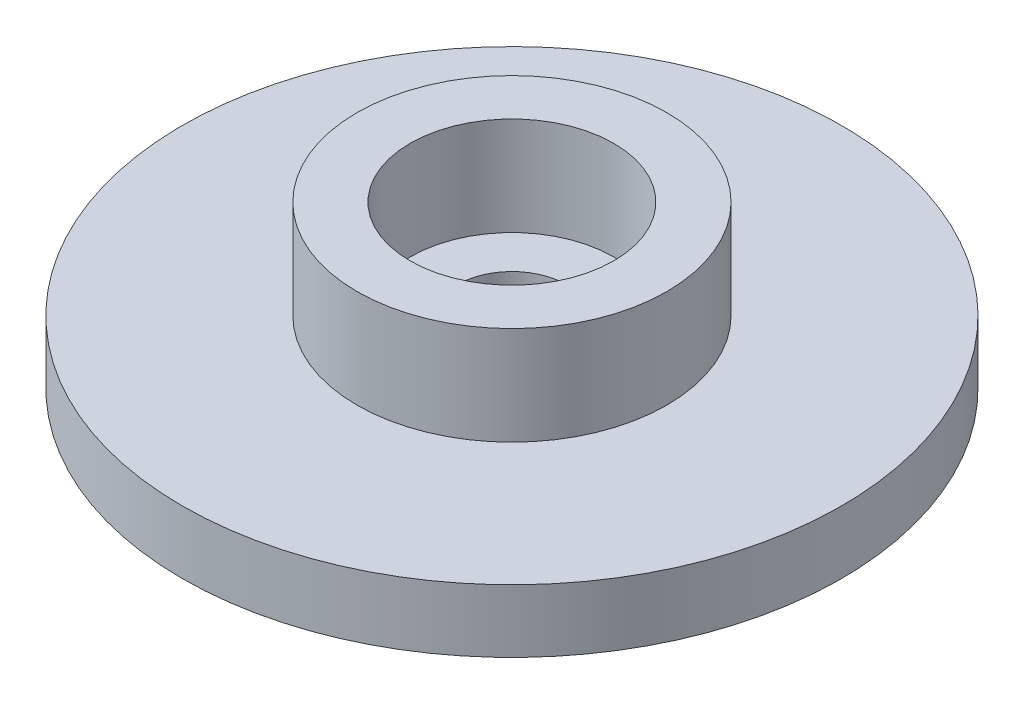
SolidWorks part; units mm, degrees
ref_plane "Front Plane" through (0, 0, 0) normal (0, 0, 1) x (1, 0, 0)
ref_plane "Top Plane" through (0, 0, 0) normal (0, 1, 0) x (1, 0, 0)
ref_plane "Right Plane" through (0, 0, 0) normal (1, 0, 0) x (0, 0, -1)
sketch "Sketch1" plane through (0, 0, 0) normal (0, 1, 0) x (1, 0, 0)
  circle A0 centre (0, 0) radius 8.509
  dimension "D1" = 17.018
extrude "Boss-Extrude1" add sketch "Sketch1" along normal blind 1.6256
sketch "Sketch2" plane through (0, 1.6256, 0) normal (0, 1, 0) x (1, 0, 0)
  circle A0 centre (0, 0) radius 4.0005
  dimension "D1" = 8.001
extrude "Boss-Extrude2" add sketch "Sketch2" along normal blind 2.54
sketch "Sketch3" plane through (0, 0, 0) normal (0, -1, 0) x (1, 0, 0)
  circle A0 centre (0, 0) radius 3.5179
  dimension "D1" = 7.0358
extrude "Boss-Extrude3" add sketch "Sketch3" along normal blind 0.762
sketch "Sketch4" plane through (0, -0.762, 0) normal (0, -1, 0) x (1, 0, 0)
  circle A0 centre (0, 0) radius 3.0099
  dimension "D1" = 6.0198
extrude "Cut-Extrude1" cut sketch "Sketch4" against normal up to surface (0.762 mm away) up to face at (0, 0, -3.5179)
sketch "Sketch5" plane through (0, 4.1656, 0) normal (0, 1, 0) x (1, 0, 0)
  circle A0 centre (0, 0) radius 2.6289
  dimension "D1" = 5.2578
extrude "Cut-Extrude2" cut sketch "Sketch5" against normal up to surface (2.54 mm away) up to face at (0, 1.6256, 4.0005)
sketch "Sketch6" plane through (0, 1.6256, 0) normal (0, 1, 0) x (1, 0, 0)
  circle A0 centre (0, 0) radius 1.397
  dimension "D1" = 2.794
extrude "Cut-Extrude3" cut sketch "Sketch6" against normal through all
